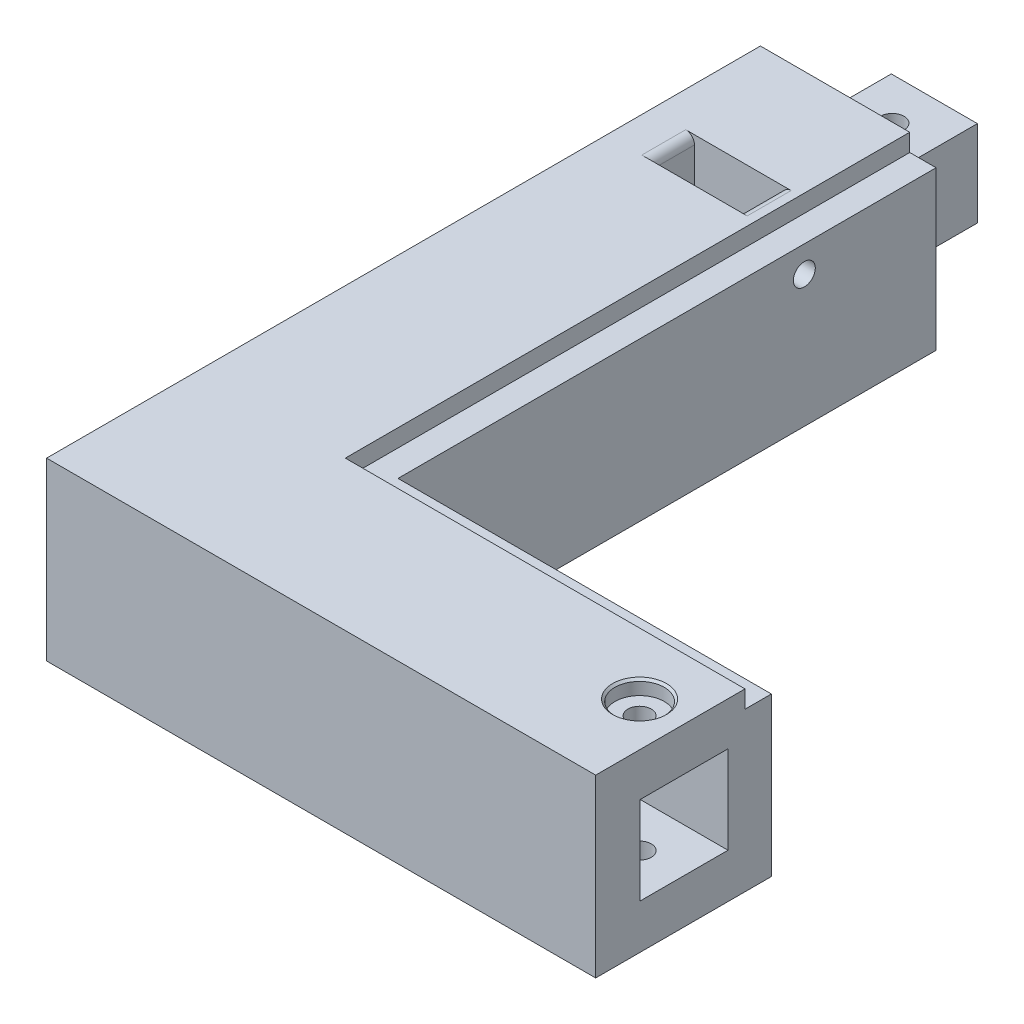
SolidWorks part; units mm, degrees
ref_plane "Front Plane" through (0, 0, 0) normal (0, 0, 1) x (1, 0, 0)
ref_plane "Top Plane" through (0, 0, 0) normal (0, 1, 0) x (1, 0, 0)
ref_plane "Right Plane" through (0, 0, 0) normal (1, 0, 0) x (0, 0, -1)
sketch "Sketch2" plane through (0, 0, 0) normal (0, 1, 0) x (1, 0, 0)
  line L0 (-50.8, 155.575) -> (0, 155.575)
  line L1 (0, 0) -> (107.95, 0)
  line L2 (0, 0) -> (0, 155.575)
  line L5 (-50.8, -50.8) -> (107.95, -50.8)
  line L6 (-50.8, -50.8) -> (-50.8, 155.575)
  line L11 (107.95, 0) -> (107.95, -50.8)
  point P5 (-50.8, -50.8)
  dimension "D1" = 206.375
  dimension "D2" = 50.8
  dimension "D3" = 50.8
  dimension "D4" = 158.75
extrude "Boss-Extrude1" add sketch "Sketch2" along normal blind 50.8
sketch "Sketch3" plane through (107.95, 0, 0) normal (1, 0, 0) x (0, 0, -1)
  line L1 (-37.9399, 12.8601) -> (-12.5399, 12.8601)
  line L2 (-37.9399, 12.8601) -> (-37.9399, 38.2601)
  line L3 (-37.9399, 38.2601) -> (-12.5399, 38.2601)
  line L4 (-12.5399, 12.8601) -> (-12.5399, 38.2601)
  line L5 (-37.9399, 12.8601) -> (-12.5399, 38.2601) construction
  line L6 (-37.9399, 38.2601) -> (-12.5399, 12.8601) construction
  point P0 (-25.2399, 25.5601)
  dimension "D1" = 25.4
extrude "Cut-Extrude1" cut sketch "Sketch3" against normal blind 25.4
sketch "Sketch6" plane through (0, 50.8, 0) normal (0, 1, 0) x (1, 0, 0)
  line L0 (107.95, 0) -> (0, 0) construction
  line L1 (107.95, -50.8) -> (107.95, 0) construction
  point P0 (95.25, -25.4)
  dimension "D1" = 25.4
  dimension "D2" = 12.7
hole_wizard "CBORE for 1/4 Binding Head Machine Screw1" positions "Sketch6" profile "Sketch7" counterbore size "1/4" standard "ANSI Inch" end condition through all
sketch "Sketch7" plane through (95.25, 50.8, 25.4) normal (1, 0, 0) x (0, 0, 1)
  line L0 (0, 0) -> (0, 50.8)
  line L1 (0, 50.8) -> (3.3782, 50.8)
  line L3 (3.3782, 50.8) -> (3.3782, 4.191)
  line L4 (7.1437, 4.191) -> (3.3782, 4.191)
  line L5 (7.1437, 4.191) -> (7.1437, 0.635)
  line L6 (7.1437, 0.635) -> (7.7788, 0)
  line L7 (7.7788, 0) -> (0, 0)
  line L8 (-7.1437, 0.635) -> (-7.7788, 0) construction
  line L11 (0, -6.35) -> (0, 107.95) construction
  dimension "Thru Hole Dia." = 6.7564
  dimension "Thru Hole Depth" = 50.8
  dimension "C'Bore Dia." = 14.2875
  dimension "C'Bore Depth" = 4.191
  dimension "Near C'Sink Dia." = 15.5575
  dimension "Near C'Sink Angle" = 90
sketch "Sketch8" plane through (0, 0, -155.575) normal (0, 0, -1) x (-1, 0, 0)
  line L0 (0, 50.8) -> (0, 0) construction
  line L1 (12.954, 12.954) -> (37.846, 12.954)
  line L2 (12.954, 12.954) -> (12.954, 37.846)
  line L3 (12.954, 37.846) -> (37.846, 37.846)
  line L4 (37.846, 12.954) -> (37.846, 37.846)
  line L5 (12.954, 12.954) -> (37.846, 37.846) construction
  line L6 (12.954, 37.846) -> (37.846, 12.954) construction
  line L8 (0, 50.8) -> (50.8, 50.8) construction
  point P0 (25.4, 25.4)
  dimension "D1" = 24.892
  dimension "D2" = 25.4
  dimension "D3" = 25.4
extrude "Boss-Extrude2" add sketch "Sketch8" along normal blind 24.892
sketch "Sketch12" plane through (0, 37.846, 0) normal (0, 1, 0) x (1, 0, 0)
  line L1 (-37.846, 180.467) -> (-37.846, 155.575) construction
  line L2 (0, 155.575) -> (-50.8, 155.575) construction
  circle A0 centre (-25.4, 168.275) radius 3.429
  dimension "D1" = 6.858
  dimension "D2" = 12.7
  dimension "D3" = 12.446
extrude "Cut-Extrude2" cut sketch "Sketch12" against normal blind 25.4
sketch "Sketch13" plane through (0, 50.8, 0) normal (0, 1, 0) x (1, 0, 0)
  line L0 (-50.8, 155.575) -> (-50.8, -50.8) construction
  line L1 (-38.1, 111.125) -> (-12.7, 111.125)
  line L2 (-38.1, 111.125) -> (-38.1, 123.825)
  line L3 (-38.1, 123.825) -> (-12.7, 123.825)
  line L4 (-12.7, 111.125) -> (-12.7, 123.825)
  line L5 (-38.1, 111.125) -> (-12.7, 123.825) construction
  line L6 (-38.1, 123.825) -> (-12.7, 111.125) construction
  line L7 (63.5, -12.7) -> (76.2, -12.7)
  line L8 (63.5, -12.7) -> (63.5, -38.1)
  line L9 (63.5, -38.1) -> (76.2, -38.1)
  line L10 (76.2, -12.7) -> (76.2, -38.1)
  line L11 (63.5, -12.7) -> (76.2, -38.1) construction
  line L12 (63.5, -38.1) -> (76.2, -12.7) construction
  line L14 (107.95, 0) -> (0, 0) construction
  line L16 (0, 155.575) -> (-50.8, 155.575) construction
  line L17 (107.95, -50.8) -> (107.95, 0) construction
  point P0 (-25.4, 117.475)
  point P5 (69.85, -25.4)
  dimension "D1" = 25.4
  dimension "D2" = 12.7
  dimension "D3" = 12.7
  dimension "D4" = 38.1
  dimension "D5" = 25.4
  dimension "D6" = 12.7
  dimension "D7" = 12.7
  dimension "D8" = 38.1
extrude "Cut-Extrude3" cut sketch "Sketch13" against normal blind 25.908 contours L3 L4 L1 L2
fillet "Fillet1" radius 2.54 2 edges at (-12.7, 50.8, -117.475) (-38.1, 50.8, -117.475)
sketch "Sketch14" plane through (-50.8, 0, 0) normal (-1, 0, 0) x (0, 0, 1)
  line L0 (-155.575, 50.8) -> (-155.575, 0) construction
  line L1 (-155.575, 50.8) -> (50.8, 50.8) construction
  circle A0 centre (-117.475, 38.1) radius 3.175
  dimension "D1" = 6.35
  dimension "D2" = 38.1
  dimension "D3" = 12.7
sketch "Sketch15" plane through (0, 0, 50.8) normal (0, 0, 1) x (1, 0, 0)
  line L0 (-50.8, 50.8) -> (107.95, 50.8) construction
  line L1 (107.95, 50.8) -> (107.95, 0) construction
  circle A0 centre (69.85, 38.1) radius 3.175
  dimension "D1" = 6.35
  dimension "D2" = 12.7
  dimension "D3" = 38.1
extrude "Cut-Extrude5" cut sketch "Sketch14" against normal through all
sketch "Sketch17" plane through (0, 50.8, 0) normal (0, 1, 0) x (1, 0, 0)
  line L0 (0, 155.575) -> (0, 0)
  line L1 (0, 0) -> (107.95, 0)
  line L2 (107.95, 0) -> (107.95, -7.62)
  line L3 (107.95, -50.8) -> (107.95, 0) construction
  line L4 (107.95, -7.62) -> (-7.62, -7.62)
  line L5 (-7.62, -7.62) -> (-7.62, 155.575)
  line L6 (0, 155.575) -> (-50.8, 155.575) construction
  line L7 (-7.62, 155.575) -> (0, 155.575)
  dimension "D1" = 7.62
  dimension "D2" = 7.62
extrude "Cut-Extrude6" cut sketch "Sketch17" against normal blind 5.08
